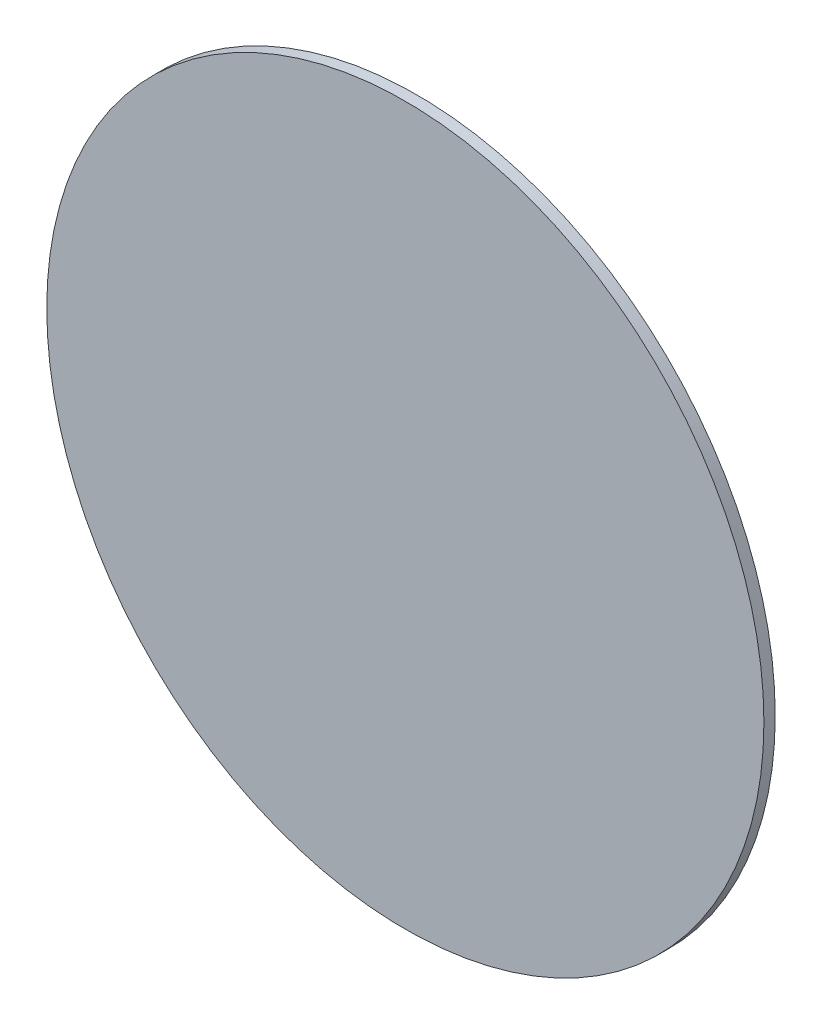
SolidWorks part; units mm, degrees
material "Alloy Steel"
ref_plane "Front Plane" through (0, 0, 0) normal (0, 0, 1) x (1, 0, 0)
ref_plane "Top Plane" through (0, 0, 0) normal (0, 1, 0) x (1, 0, 0)
ref_plane "Right Plane" through (0, 0, 0) normal (1, 0, 0) x (0, 0, -1)
sketch "Sketch1" plane through (0, 0, 0) normal (0, 0, 1) x (1, 0, 0)
  circle A0 centre (0, 0) radius 95
extrude "Boss-Extrude1" add sketch "Sketch1" along normal blind 3
